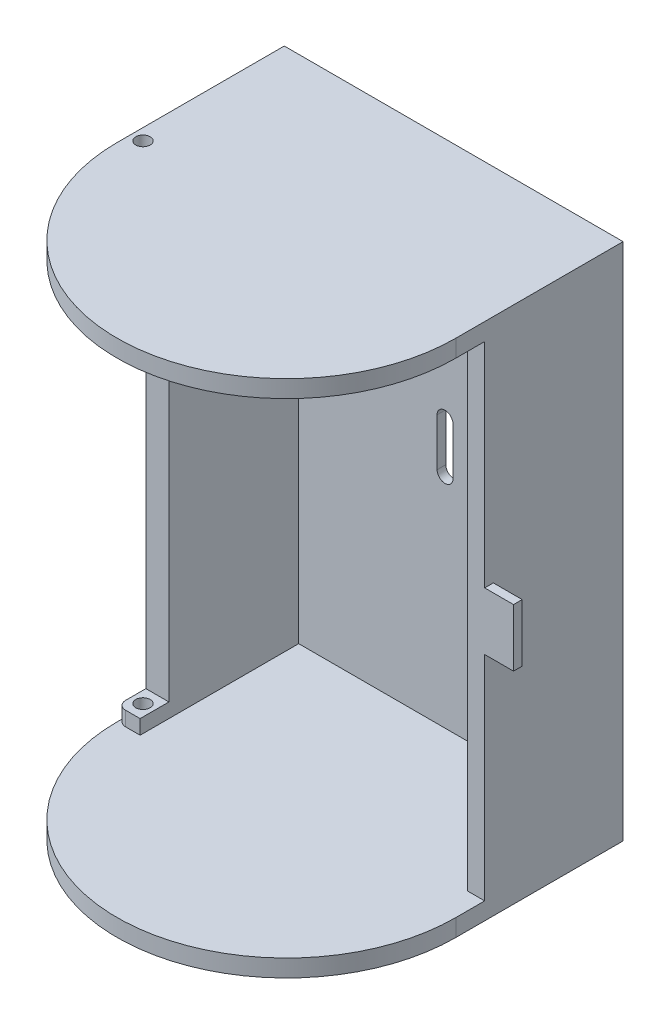
SolidWorks part; units mm, degrees
ref_plane "前基準面" through (0, 0, 0) normal (0, 0, 1) x (1, 0, 0)
ref_plane "上基準面" through (0, 0, 0) normal (0, 1, 0) x (1, 0, 0)
ref_plane "右基準面" through (0, 0, 0) normal (1, 0, 0) x (0, 0, -1)
sketch "草圖2" plane through (0, 0, 0) normal (0, 0, 1) x (1, 0, 0)
  line L1 (-58.75, 90) -> (58.75, 90)
  line L2 (-58.75, 90) -> (-58.75, -90)
  line L3 (-58.75, -90) -> (58.75, -90)
  line L4 (58.75, 90) -> (58.75, -90)
  line L5 (-58.75, 90) -> (58.75, -90) construction
  line L6 (-58.75, -90) -> (58.75, 90) construction
  point P0 (0, 0)
  dimension "D1" = 117.5
  dimension "D2" = 180
extrude "填料-伸長2" add sketch "草圖2" along normal blind 3
sketch "草圖4" plane through (0, -90, 0) normal (0, -1, 0) x (1, 0, 0)
  line L0 (-58.75, 3) -> (-58.75, 58)
  line L14 (58.75, 58) -> (58.75, 3)
  line L15 (58.75, 3) -> (-58.75, 3)
  line L16 (58.75, 3) -> (58.75, 0) construction
  arc A1 (-58.75, 58) -> (58.75, 58) centre (0, 58) cw
  dimension "D2" = 55
extrude "填料-伸長5" add sketch "草圖4" against normal blind 6
sketch "草圖5" plane through (0, 90, 0) normal (0, 1, 0) x (1, 0, 0)
  line L0 (-58.75, -3) -> (-58.75, -58)
  line L2 (58.75, -58) -> (58.75, -3)
  line L3 (58.75, -3) -> (-58.75, -3)
  arc A0 (-58.75, -58) -> (58.75, -58) centre (0, -58) ccw
extrude "填料-伸長6" add sketch "草圖5" against normal blind 6
sketch "草圖7" plane through (-58.75, 0, 0) normal (-1, 0, 0) x (0, 0, 1)
  line L0 (3, 84) -> (58, 84)
  line L1 (58, 84) -> (58, 79)
  line L2 (58, 79) -> (48, 79)
  line L4 (48, 79) -> (48, -79)
  line L6 (48, -79) -> (58, -79)
  line L7 (58, -79) -> (58, -84)
  line L8 (58, -84) -> (3, -84)
  line L9 (3, -84) -> (3, 84)
  dimension "D1" = 10
  dimension "D2" = 5
extrude "填料-伸長8" add sketch "草圖7" against normal blind 8
sketch "草圖8" plane through (0, 79, 0) normal (0, -1, 0) x (1, 0, 0)
  line L0 (-58.75, 48) -> (-58.75, 58) construction
  line L1 (-50.75, 58) -> (-58.75, 58) construction
  circle A0 centre (-54.75, 53) radius 2.5
  dimension "D1" = 5
  dimension "D2" = 4
  dimension "D3" = 5
extrude "除料-伸長1" cut sketch "草圖8" against normal blind 20 and the other way blind 188
fillet "圓角1" radius 3 2 edges at (-58.75, -81.5, 58) (-58.75, 81.5, 58)
sketch "草圖10" plane through (0, 0, 3) normal (0, 0, 1) x (1, 0, 0)
  line L0 (52.75, 84) -> (58.75, 84)
  line L1 (58.75, 84) -> (58.75, -84)
  line L2 (58.75, -84) -> (52.75, -84)
  line L3 (52.75, -84) -> (52.75, 84)
  dimension "D1" = 6
extrude "填料-伸長9" add sketch "草圖10" along normal up to surface (45 mm away) up to face at (-54.75, 0, 48)
sketch "草圖11" plane through (0, 0, 0) normal (0, 0, -1) x (-1, 0, 0)
  line L0 (-2.75, 34.25) -> (-2.75, 17.75)
  line L1 (-6.25, 40) -> (6.25, 40)
  line L2 (-6.25, 40) -> (-6.25, -40)
  line L3 (-6.25, -40) -> (6.25, -40)
  line L4 (6.25, 40) -> (6.25, -40)
  line L5 (-6.25, 40) -> (-2.6715, 17.0977) construction
  line L6 (6.25, 0) -> (13.6777, 0) construction
  line L7 (2.75, 34.25) -> (2.75, 17.75)
  line L8 (0, 0) -> (2.75, 0) construction
  line L10 (2.75, 8.7454) -> (2.75, -7.7546)
  line L11 (-2.75, 8.7454) -> (-2.75, -7.7546)
  line L12 (2.6715, 17.0977) -> (6.25, 40) construction
  line L13 (-2.75, 8.7454) -> (2.75, -7.7546) construction
  line L14 (2.75, 8.7454) -> (-2.75, -7.7546) construction
  line L15 (-58.75, -90) -> (-58.75, 90) construction
  arc A1 (2.75, 34.25) -> (-2.75, 34.25) centre (0, 34.25) ccw
  arc A2 (-2.75, 17.75) -> (2.75, 17.75) centre (0, 17.75) ccw
  arc A3 (2.75, 8.7454) -> (-2.75, 8.7454) centre (0, 8.7454) ccw
  arc A4 (-2.75, -7.7546) -> (2.75, -7.7546) centre (0, -7.7546) ccw
  point P0 (0, 0)
  point P16 (0, 0)
  point P21 (0, -10.5046)
  point P22 (0, 0)
  point P29 (-58.75, 0)
  dimension "D1" = 80
  dimension "D3" = 5.5
  dimension "D4" = 22
  dimension "D5" = 22
  dimension "D6" = 2.75
  dimension "D2" = 12.5
extrude "除料-伸長2" cut sketch "草圖11" against normal through all
sketch "草圖12" plane through (58.75, 0, 0) normal (1, 0, 0) x (0, 0, -1)
  line L0 (-48, -84) -> (-48, 84) construction
  line L1 (-48, 10) -> (-45, 10)
  line L2 (-48, 10) -> (-48, -10)
  line L3 (-48, -10) -> (-45, -10)
  line L4 (-45, 10) -> (-45, -10)
  line L5 (-48, 10) -> (-45, -10) construction
  line L6 (-48, -10) -> (-45, 10) construction
  point P0 (-46.5, 0)
  dimension "D1" = 20
  dimension "D2" = 3
extrude "填料-伸長10" add sketch "草圖12" along normal blind 10
